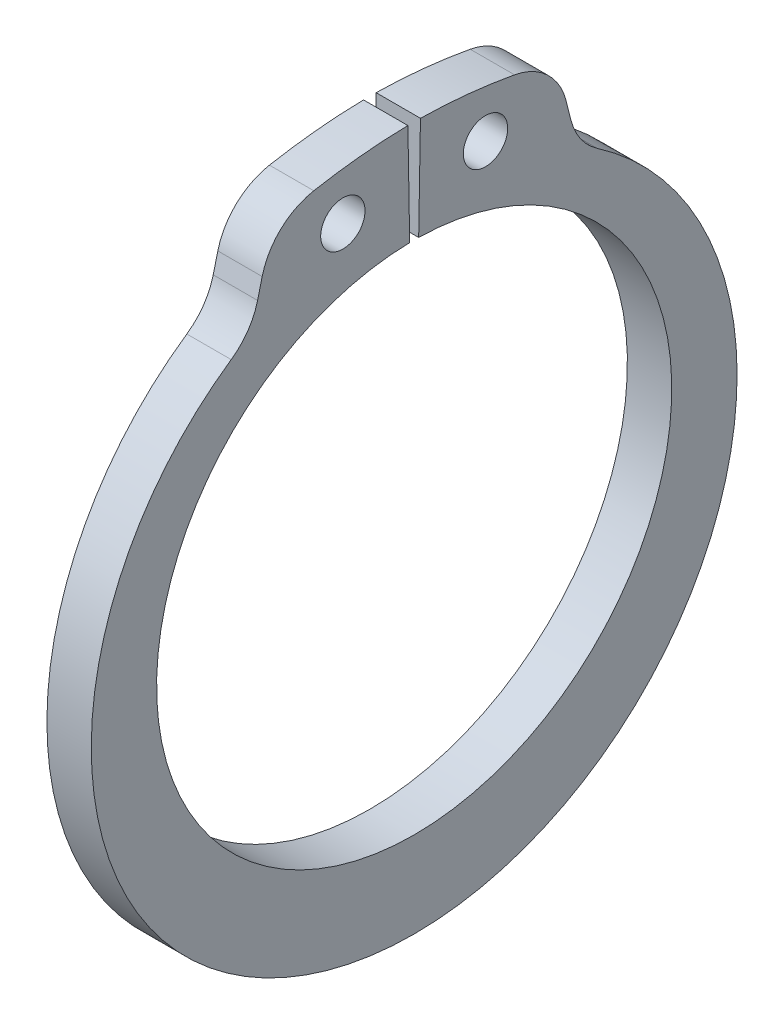
SolidWorks part; units mm, degrees
material "Cast Carbon Steel"
ref_plane "Front" through (0, 0, 0) normal (0, 0, 1) x (1, 0, 0)
ref_plane "Top" through (0, 0, 0) normal (0, 1, 0) x (1, 0, 0)
ref_plane "Right" through (0, 0, 0) normal (1, 0, 0) x (0, 0, -1)
sketch "Sketch1" plane through (0, 0, 0) normal (1, 0, 0) x (0, 0, -1)
  line L0 (0, 0) -> (0, 11.5062) construction
  line L1 (-0.2008, 11.5044) -> (-0.2806, 16.0758)
  line L2 (-0.2806, 16.0758) -> (-6.1704, 15.9729) construction
  line L3 (-6.1704, 15.9729) -> (-7.2765, 11.5368) construction
  line L4 (0.2806, 16.0758) -> (0.2008, 11.5044)
  line L5 (0.2806, 16.0758) -> (6.1704, 15.9729) construction
  line L6 (6.1704, 15.9729) -> (7.2765, 11.5368) construction
  line L7 (-7.2765, 11.5368) -> (-6.1383, 9.7321) construction
  line L8 (7.2765, 11.5368) -> (6.1383, 9.7321) construction
  line L9 (0, -11.5062) -> (0, -15.3416) construction
  line L10 (-6.1704, 15.9729) -> (-0.2008, 11.5044) construction
  line L11 (-11.5062, 0) -> (11.5062, 0) construction
  line L12 (0, 11.5062) -> (0, 16.0782) construction
  line L13 (6.3535, 15.2385) -> (7.2765, 11.5368)
  line L14 (-6.3535, 15.2385) -> (-7.2765, 11.5368)
  circle A0 centre (0, 0) radius 11.5062 construction
  arc A1 (-0.2008, 11.5044) -> (0.2008, 11.5044) centre (0, 0) ccw
  circle A2 centre (0, -0.9175) radius 14.4241 construction
  circle A3 centre (0, 0) radius 16.51 construction
  circle A4 centre (-3.1856, 13.7387) radius 0.9906
  circle A5 centre (3.1856, 13.7387) radius 0.9906
  arc A6 (-7.2765, 11.5368) -> (7.2765, 11.5368) centre (0, -0.9175) ccw
  arc A7 (0.2806, 16.0758) -> (6.3535, 15.2385) centre (-0.168, -9.6219) cw
  arc A8 (-0.2806, 16.0758) -> (-6.3535, 15.2385) centre (0.168, -9.6219) ccw
  dimension "D1" = 75
  dimension "A" = 23.0124
  dimension "L" = 33.02
  dimension "Hole" = 1.9812
  dimension "Smin" = 2.1336
  dimension "Smax" = 3.8354
  dimension "H" = 4.572
  dimension "Angle" = 1
extrude "Extrude1" add sketch "Sketch1" along normal mid plane 1.9812
fillet "Fillet1" radius 2.921 4 edges at (0, 11.5368, 7.2765) (0, 15.2385, 6.3535) (0, 15.2385, -6.3535) (0, 11.5368, -7.2765)
sketch "Sketch2" plane through (0, 0, 0) normal (0, 0, 1) x (1, 0, 0)
  line L0 (-5.461, 0) -> (16.383, 0)
  line L1 (16.383, 0) -> (16.383, -12.7)
  line L3 (16.383, -12.7) -> (1.0922, -12.7)
  line L4 (1.0922, -12.7) -> (1.0922, -11.9126)
  line L5 (1.0922, -11.9126) -> (-1.0922, -11.9126)
  line L6 (-1.0922, -11.9126) -> (-1.0922, -12.7)
  line L7 (-1.0922, -12.7) -> (-5.461, -12.7) construction
  line L8 (-5.461, -12.7) -> (-5.461, 0) construction
  line L9 (0, -11.9126) -> (0, 0) construction
  line L10 (16.383, 0) -> (14.0551, 0) construction
  line L11 (-1.0922, -12.7) -> (-5.0673, -12.7)
  line L12 (-5.0673, -12.7) -> (-5.461, -12.3063)
  line L13 (-5.461, -12.3063) -> (-5.461, 0)
  point P14 (-1.0922, -12.3063)
  dimension "Dg" = 23.8252
  dimension "Ds" = 25.4
  dimension "D2" = 21.844
  dimension "W" = 2.1844
  dimension "D3" = 5.461
  dimension "D4" = 45
equation "\"D2@Sketch2\" = \"W@Sketch2\"*10"
equation "\"D3@Sketch2\" = \"D2@Sketch2\"/4"
